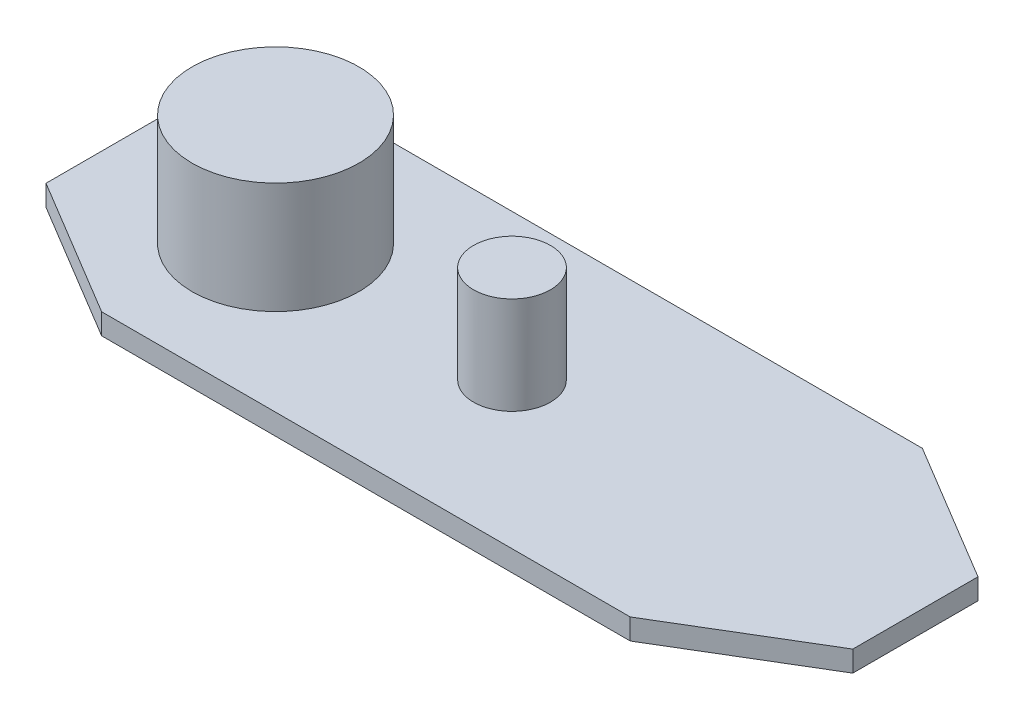
SolidWorks part; units mm, degrees
ref_plane "Front Plane" through (0, 0, 0) normal (0, 0, 1) x (1, 0, 0)
ref_plane "Top Plane" through (0, 0, 0) normal (0, 1, 0) x (1, 0, 0)
ref_plane "Right Plane" through (0, 0, 0) normal (1, 0, 0) x (0, 0, -1)
sketch "Sketch1" plane through (0, 0, 0) normal (0, 1, 0) x (1, 0, 0)
  line L0 (-19, 10.5) -> (-19, -10.5) construction
  line L1 (-19, 10.5) -> (19, 10.5)
  line L2 (-29, 4.5) -> (-29, -4.5)
  line L3 (-19, -10.5) -> (19, -10.5)
  line L4 (29, 4.5) -> (29, -4.5)
  line L7 (-19, 10.5) -> (-29, 4.5)
  line L8 (-19, -10.5) -> (-29, -4.5)
  line L9 (0, 10.5) -> (0, -10.5) construction
  line L10 (19, 10.5) -> (29, 4.5)
  line L11 (19, -10.5) -> (29, -4.5)
  point P0 (0, 0)
  dimension "D3" = 10
  dimension "D4" = 6
  dimension "D5" = 6
extrude "Boss-Extrude1" add sketch "Sketch1" along normal blind 1.5
sketch "Sketch2" plane through (0, 1.5, 0) normal (0, 1, 0) x (1, 0, 0)
  line L0 (-29, 4.5) -> (-29, -4.5) construction
  circle A0 centre (-17, 0) radius 6
  dimension "D1" = 12
  dimension "D2" = 12
extrude "Boss-Extrude2" add sketch "Sketch2" along normal blind 8
sketch "Sketch3" plane through (0, 1.5, 0) normal (0, 1, 0) x (1, 0, 0)
  circle A0 centre (0, 0) radius 2.7641
extrude "Boss-Extrude3" add sketch "Sketch3" along normal blind 7
